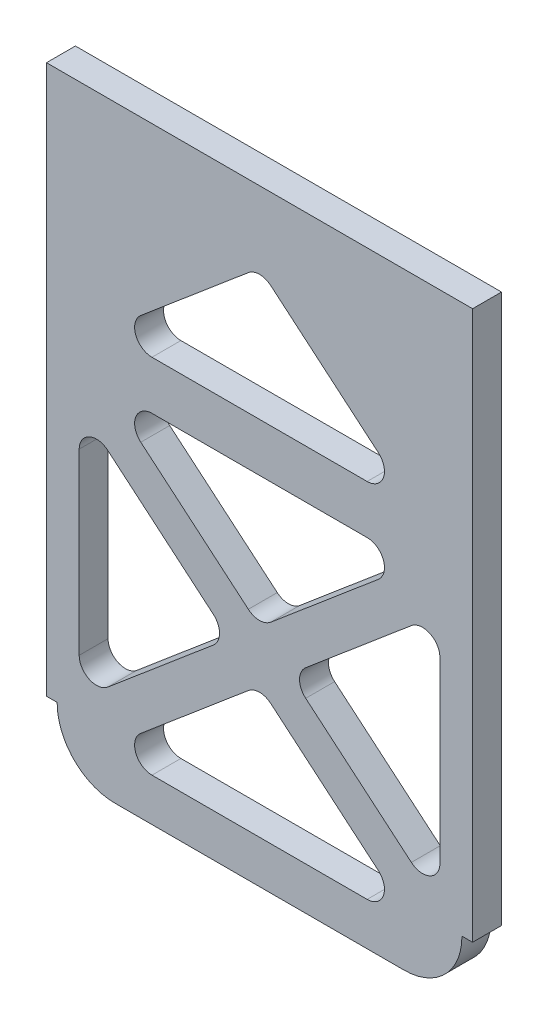
SolidWorks part; units mm, degrees
ref_plane "Front Plane" through (0, 0, 0) normal (0, 0, 1) x (1, 0, 0)
ref_plane "Top Plane" through (0, 0, 0) normal (0, 1, 0) x (1, 0, 0)
ref_plane "Right Plane" through (0, 0, 0) normal (1, 0, 0) x (0, 0, -1)
sketch "Sketch1" plane through (0, 0, 0) normal (0, 0, 1) x (1, 0, 0)
  line L0 (-40, 55) -> (-35, 55) construction
  line L1 (-40, 55) -> (-35, 55)
  line L3 (-36.85, 55) -> (36.85, 55)
  line L4 (-24.85, -50) -> (24.85, -50)
  line L5 (34.85, -40) -> (34.85, 20)
  line L6 (34.85, 20) -> (-34.85, 20)
  line L7 (-34.85, 20) -> (-34.85, -40)
  line L8 (-24.85, -50) -> (24.85, -50) construction
  line L9 (34.85, -40) -> (34.85, 20) construction
  line L10 (34.85, 20) -> (-34.85, 20) construction
  line L11 (-34.85, 20) -> (-34.85, -40) construction
  line L12 (-36.85, 55) -> (-36.85, -50)
  line L13 (-36.85, -50) -> (36.85, -50)
  line L14 (36.85, 55) -> (36.85, -50)
  arc A2 (-34.85, -40) -> (-24.85, -50) centre (-24.85, -40) ccw
  arc A3 (24.85, -50) -> (34.85, -40) centre (24.85, -40) ccw
  arc A4 (-34.85, -40) -> (-24.85, -50) centre (-24.85, -40) ccw construction
  arc A5 (24.85, -50) -> (34.85, -40) centre (24.85, -40) ccw construction
  point P14 (0, 55)
  dimension "D2" = 2
  dimension "D1" = 0
extrude "Boss-Extrude1" add sketch "Sketch1" along normal blind 5 contours L14 L3 L1 L12 L13
sketch "Sketch2" plane through (0, 0, 0) normal (0, 0, -1) x (-1, 0, 0)
  line L0 (-18.6062, -42.5972) -> (18.6062, -42.5972) construction
  line L1 (-1.9361, -21.5866) -> (-20.5422, -37.3056) construction
  line L2 (20.5422, -37.3056) -> (1.9361, -21.5866) construction
  line L3 (7.981, -17.7917) -> (26.2581, -33.2327) construction
  line L4 (31.1942, -0.059) -> (31.1942, -30.941) construction
  line L5 (26.2581, 2.2327) -> (7.981, -13.2083) construction
  line L6 (-31.1942, -0.059) -> (-31.1942, -30.941) construction
  line L7 (-26.2581, -33.2327) -> (-7.981, -17.7917) construction
  line L8 (-7.981, -13.2083) -> (-26.2581, 2.2327) construction
  line L9 (18.6062, 11.5972) -> (-18.6062, 11.5972) construction
  line L10 (1.9361, -9.4134) -> (20.5422, 6.3056) construction
  line L11 (-20.5422, 6.3056) -> (-1.9361, -9.4134) construction
  line L12 (-18.6062, -42.5972) -> (18.6062, -42.5972)
  line L13 (-1.9361, -21.5866) -> (-20.5422, -37.3056)
  line L14 (20.5422, -37.3056) -> (1.9361, -21.5866)
  line L15 (7.981, -17.7917) -> (26.2581, -33.2327)
  line L16 (31.1942, -0.059) -> (31.1942, -30.941)
  line L17 (26.2581, 2.2327) -> (7.981, -13.2083)
  line L18 (-31.1942, -0.059) -> (-31.1942, -30.941)
  line L19 (-26.2581, -33.2327) -> (-7.981, -17.7917)
  line L20 (-7.981, -13.2083) -> (-26.2581, 2.2327)
  line L21 (18.6062, 11.5972) -> (-18.6062, 11.5972)
  line L22 (1.9361, -9.4134) -> (20.5422, 6.3056)
  line L23 (-20.5422, 6.3056) -> (-1.9361, -9.4134)
  line L24 (34.85, 20) -> (-34.85, 20) construction
  line L25 (34.85, 20) -> (-34.85, 20) construction
  line L26 (0, 20) -> (0, 11.5972) construction
  line L27 (0, 15.7986) -> (-34.85, 15.7986) construction
  line L28 (18.6062, 20) -> (-18.6062, 20)
  line L29 (1.9361, 41.0107) -> (20.5422, 25.2917)
  line L30 (-20.5422, 25.2917) -> (-1.9361, 41.0107)
  arc A0 (-20.5422, -37.3056) -> (-18.6062, -42.5972) centre (-18.6062, -39.5972) ccw construction
  arc A1 (1.9361, -21.5866) -> (-1.9361, -21.5866) centre (0, -23.8782) ccw construction
  arc A2 (18.6062, -42.5972) -> (20.5422, -37.3056) centre (18.6062, -39.5972) ccw construction
  arc A3 (26.2581, -33.2327) -> (31.1942, -30.941) centre (28.1942, -30.941) ccw construction
  arc A4 (31.1942, -0.059) -> (26.2581, 2.2327) centre (28.1942, -0.059) ccw construction
  arc A5 (7.981, -13.2083) -> (7.981, -17.7917) centre (9.9171, -15.5) ccw construction
  arc A6 (-26.2581, 2.2327) -> (-31.1942, -0.059) centre (-28.1942, -0.059) ccw construction
  arc A7 (-31.1942, -30.941) -> (-26.2581, -33.2327) centre (-28.1942, -30.941) ccw construction
  arc A8 (-7.981, -17.7917) -> (-7.981, -13.2083) centre (-9.9171, -15.5) ccw construction
  arc A9 (-18.6062, 11.5972) -> (-20.5422, 6.3056) centre (-18.6062, 8.5972) ccw construction
  arc A10 (20.5422, 6.3056) -> (18.6062, 11.5972) centre (18.6062, 8.5972) ccw construction
  arc A11 (-1.9361, -9.4134) -> (1.9361, -9.4134) centre (0, -7.1218) ccw construction
  arc A12 (-20.5422, -37.3056) -> (-18.6062, -42.5972) centre (-18.6062, -39.5972) ccw
  arc A13 (1.9361, -21.5866) -> (-1.9361, -21.5866) centre (0, -23.8782) ccw
  arc A14 (18.6062, -42.5972) -> (20.5422, -37.3056) centre (18.6062, -39.5972) ccw
  arc A15 (26.2581, -33.2327) -> (31.1942, -30.941) centre (28.1942, -30.941) ccw
  arc A16 (31.1942, -0.059) -> (26.2581, 2.2327) centre (28.1942, -0.059) ccw
  arc A17 (7.981, -13.2083) -> (7.981, -17.7917) centre (9.9171, -15.5) ccw
  arc A18 (-26.2581, 2.2327) -> (-31.1942, -0.059) centre (-28.1942, -0.059) ccw
  arc A19 (-31.1942, -30.941) -> (-26.2581, -33.2327) centre (-28.1942, -30.941) ccw
  arc A20 (-7.981, -17.7917) -> (-7.981, -13.2083) centre (-9.9171, -15.5) ccw
  arc A21 (-18.6062, 11.5972) -> (-20.5422, 6.3056) centre (-18.6062, 8.5972) ccw
  arc A22 (20.5422, 6.3056) -> (18.6062, 11.5972) centre (18.6062, 8.5972) ccw
  arc A23 (-1.9361, -9.4134) -> (1.9361, -9.4134) centre (0, -7.1218) ccw
  arc A24 (20.5422, 25.2917) -> (18.6062, 20) centre (18.6062, 23) cw
  arc A25 (-1.9361, 41.0107) -> (1.9361, 41.0107) centre (0, 38.719) cw
  arc A26 (-18.6062, 20) -> (-20.5422, 25.2917) centre (-18.6062, 23) cw
extrude "Cut-Extrude1" cut sketch "Sketch2" against normal up to next
sketch "Sketch7" plane through (0, 0, 5) normal (0, 0, 1) x (1, 0, 0)
  line L0 (-36.85, -50) -> (36.85, -50) construction
  line L1 (-36.85, -50) -> (36.85, -50)
  line L2 (-36.85, 55) -> (-36.85, -50) construction
  line L3 (-36.85, 55) -> (-36.85, -50)
  line L4 (-35, -40) -> (-35, -39.9)
  line L5 (-35, -39.9) -> (-36.85, -39.9)
  line L6 (0, -2.75) -> (0, 2.75) construction
  line L7 (36.85, 55) -> (36.85, -50)
  line L8 (35, -39.9) -> (36.85, -39.9)
  line L9 (35, -40) -> (35, -39.9)
  arc A0 (-35, -40) -> (-25, -50) centre (-25, -40) ccw construction
  arc A1 (-35, -40) -> (-25, -50) centre (-25, -40) ccw
  arc A2 (35, -40) -> (25, -50) centre (25, -40) cw
  line M34 (36.85, -50) -> (36.85, 55)
  line M37 (-36.85, -50) -> (36.85, -50)
  dimension "D1" = 0.1
extrude "Cut-Extrude2" cut sketch "Sketch7" against normal through all contours A1 L4 L5 L3 M37 | L9 A2 L8 M37 M34
